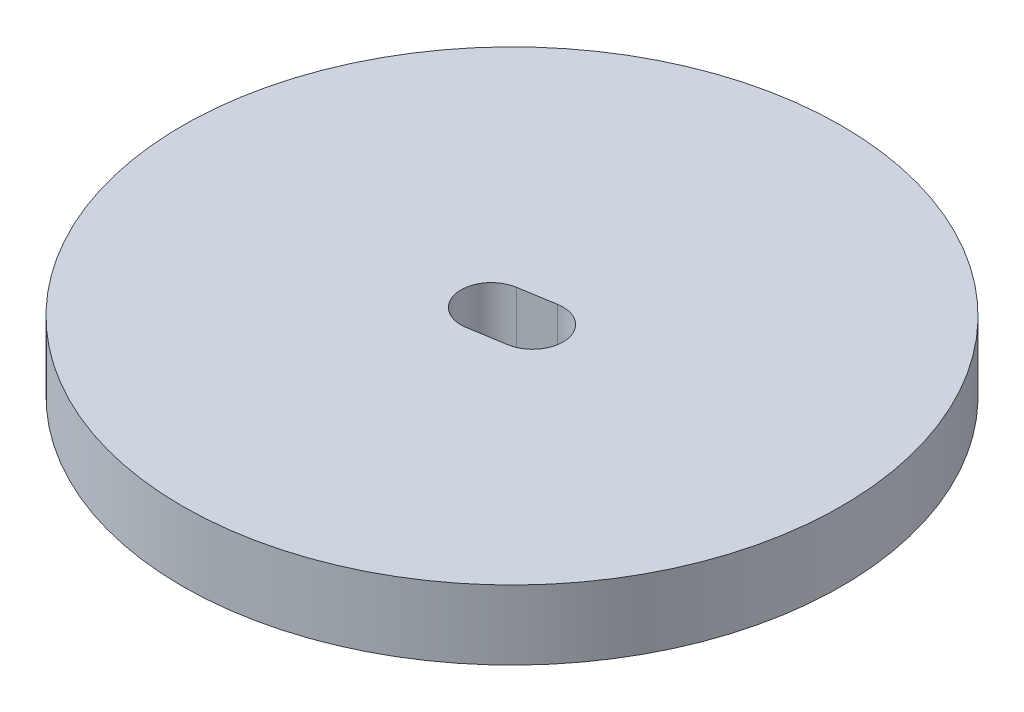
SolidWorks part; units mm, degrees
ref_plane "正面" through (0, 0, 0) normal (0, 0, 1) x (1, 0, 0)
ref_plane "平面" through (0, 0, 0) normal (0, 1, 0) x (1, 0, 0)
ref_plane "右側面" through (0, 0, 0) normal (1, 0, 0) x (0, 0, -1)
sketch "ｽｹｯﾁ1" plane through (0, 0, 0) normal (0, 1, 0) x (1, 0, 0)
  circle A0 centre (0, 0) radius 19
  dimension "D1" = 38
extrude "ﾎﾞｽ - 押し出し1" add sketch "ｽｹｯﾁ1" along normal blind 4
sketch "ｽｹｯﾁ2" plane through (0, 4, 0) normal (0, 1, 0) x (1, 0, 0)
  line L0 (-1.0231, -0.1681) -> (1.0231, 0.1681) construction
  line L1 (-1.3068, 1.5588) -> (0.7394, 1.8949)
  line L2 (-0.7394, -1.8949) -> (1.3068, -1.5588)
  arc A0 (-1.3068, 1.5588) -> (-0.7394, -1.8949) centre (-1.0231, -0.1681) ccw
  arc A1 (1.3068, -1.5588) -> (0.7394, 1.8949) centre (1.0231, 0.1681) ccw
  point P2 (0, 0)
  point P7 (-2.75, -0.4518)
  point P8 (2.75, 0.4518)
  point P9 (3.4766, 2.4843)
  dimension "D2" = 5.5
  dimension "D1" = 3.5
extrude "ｶｯﾄ - 押し出し1" cut sketch "ｽｹｯﾁ2" against normal through all
